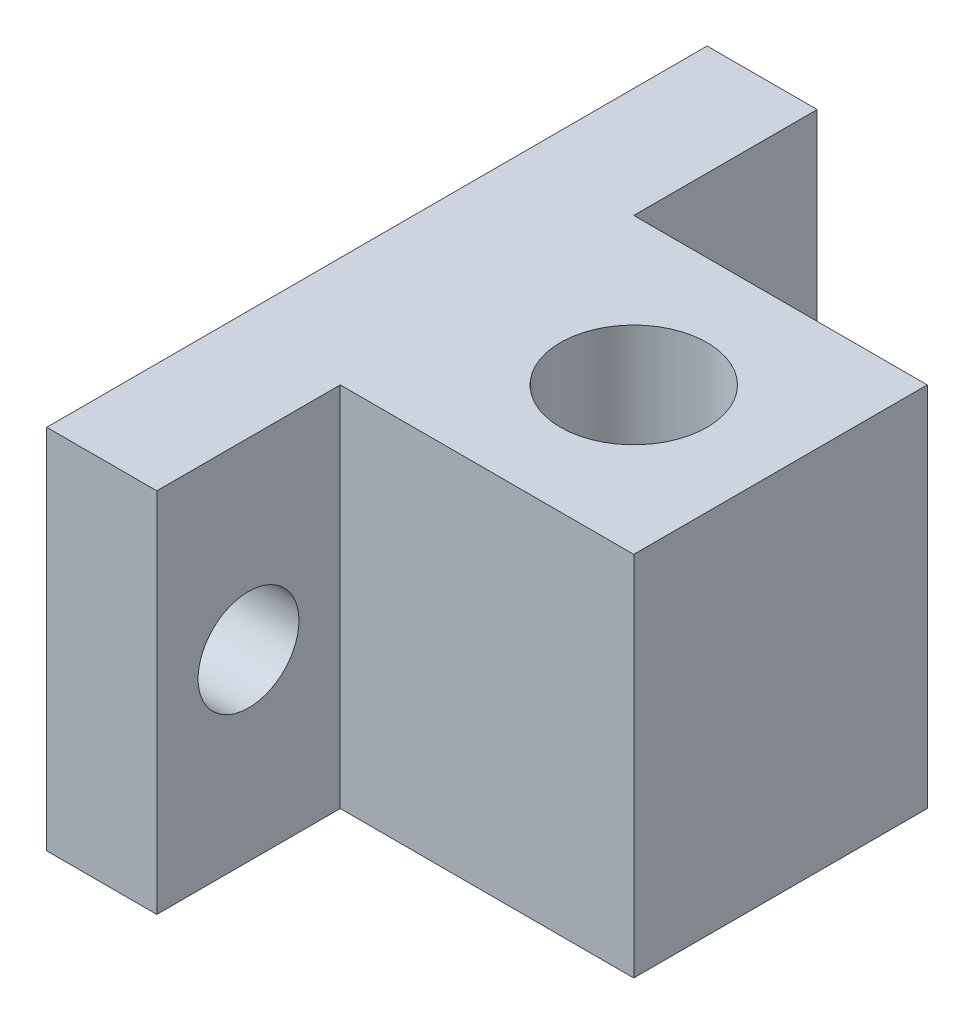
SolidWorks part; units mm, degrees
ref_plane "Front Plane" through (0, 0, 0) normal (0, 0, 1) x (1, 0, 0)
ref_plane "Top Plane" through (0, 0, 0) normal (0, 1, 0) x (1, 0, 0)
ref_plane "Right Plane" through (0, 0, 0) normal (1, 0, 0) x (0, 0, -1)
sketch "Sketch1" plane through (0, 0, 0) normal (0, 1, 0) x (1, 0, 0)
  line L0 (0, 0) -> (0, 36)
  line L1 (0, 36) -> (6, 36)
  line L2 (6, 36) -> (6, 26)
  line L3 (6, 26) -> (22, 26)
  line L4 (22, 26) -> (22, 10)
  line L5 (22, 10) -> (6, 10)
  line L6 (6, 10) -> (6, 0)
  line L7 (6, 0) -> (0, 0)
  circle A0 centre (14, 18) radius 4
  point P11 (6, 5)
  dimension "D1" = 8
  dimension "D2" = 16
  dimension "D3" = 8
  dimension "D4" = 22
  dimension "D5" = 6
  dimension "D6" = 6
  dimension "D7" = 36
  dimension "D8" = 8
  dimension "D9" = 10
extrude "Boss-Extrude1" add sketch "Sketch1" along normal blind 20
sketch "Sketch2" plane through (6, 0, 0) normal (1, 0, 0) x (0, 0, -1)
  line L0 (36, 20) -> (36, 0) construction
  line L2 (0, 0) -> (10, 0) construction
  circle A0 centre (5, 10) radius 2.75
  circle A1 centre (31, 10) radius 2.75
  dimension "D1" = 5.5
  dimension "D2" = 5.5
  dimension "D3" = 26
  dimension "D4" = 5
  dimension "D5" = 10
extrude "Cut-Extrude1" cut sketch "Sketch2" against normal blind 10
